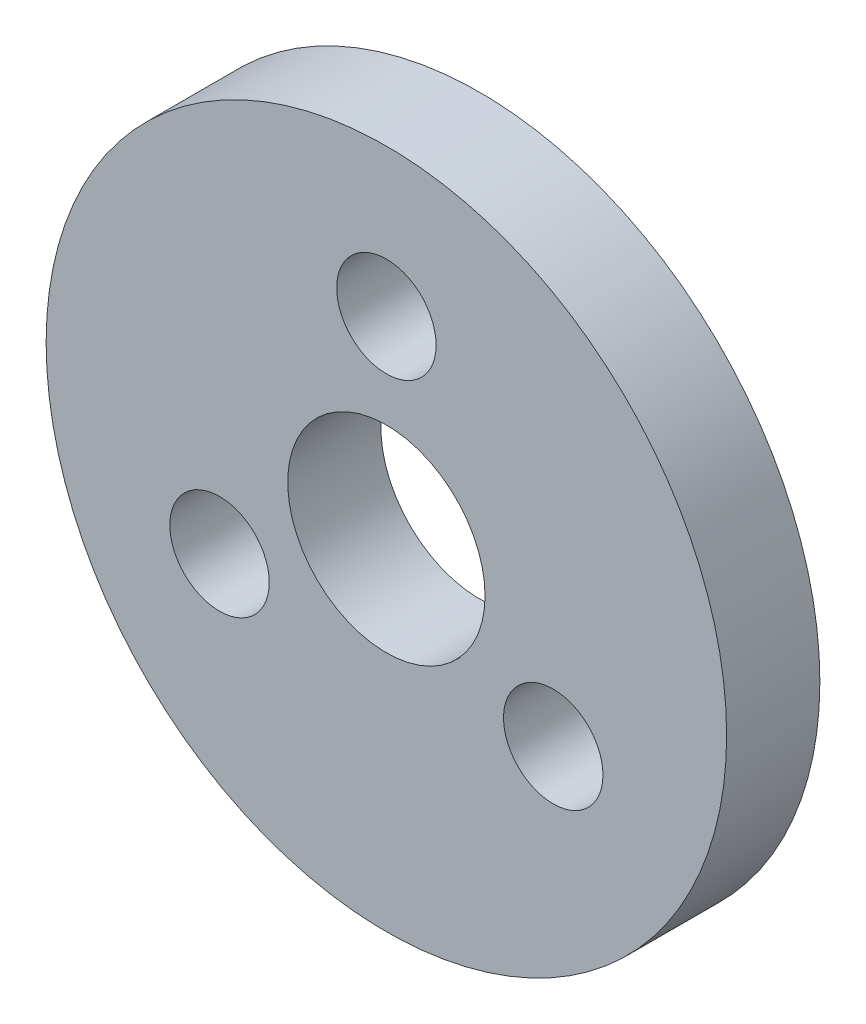
SolidWorks part; units mm, degrees
ref_plane "Front Plane" through (0, 0, 0) normal (0, 0, 1) x (1, 0, 0)
ref_plane "Top Plane" through (0, 0, 0) normal (0, 1, 0) x (1, 0, 0)
ref_plane "Right Plane" through (0, 0, 0) normal (1, 0, 0) x (0, 0, -1)
sketch "Sketch1" plane through (0, 0, 0) normal (0, 0, 1) x (1, 0, 0)
  circle A0 centre (0, 0) radius 10.95
  circle A1 centre (0, 0) radius 3.175
  dimension "D1" = 6.35
  dimension "D2" = 21.9
extrude "Boss-Extrude1" add sketch "Sketch1" along normal blind 3
sketch "Sketch2" plane through (0, 0, 3) normal (0, 0, 1) x (1, 0, 0)
  line L1 (5.3694, -3.1) -> (0, 6.2) construction
  line L2 (0, 6.2) -> (-5.3694, -3.1) construction
  line L3 (-5.3694, -3.1) -> (5.3694, -3.1) construction
  circle A0 centre (0, 0) radius 6.2 construction
  dimension "D1" = 12.4
hole_wizard "M3 Clearance Hole1" positions "Sketch3" profile "Sketch4" hole size "M3" standard "ANSI Metric" end condition through all
sketch "Sketch3" plane through (0, 0, 3) normal (0, 0, 1) x (1, 0, 0)
  point P0 (0, 6.2)
  point P3 (-5.3694, -3.1)
  point P6 (5.3694, -3.1)
sketch "Sketch4" plane through (0, 6.2, 3) normal (1, 0, 0) x (0, -1, 0)
  line L0 (0, 0) -> (0, 3)
  line L1 (0, 3) -> (1.6, 3)
  line L2 (1.6, 3) -> (1.6, 0)
  line L5 (1.6, 0) -> (0, 0)
  line L11 (0, -6.35) -> (0, 107.95) construction
  dimension "Thru Hole Dia." = 3.2
  dimension "Thru Hole Depth" = 3
